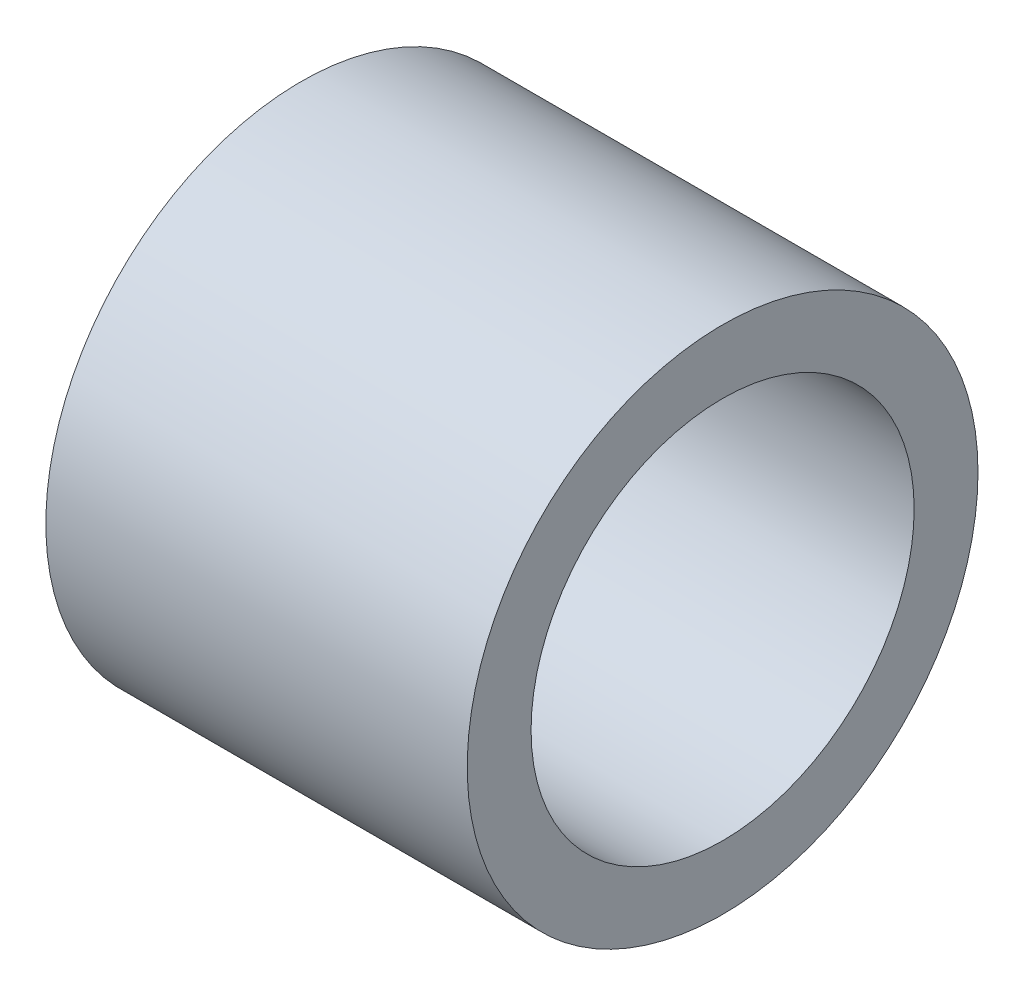
SolidWorks part; units mm, degrees
ref_plane "Front Plane" through (0, 0, 0) normal (0, 0, 1) x (1, 0, 0)
ref_plane "Top Plane" through (0, 0, 0) normal (0, 1, 0) x (1, 0, 0)
ref_plane "Right Plane" through (0, 0, 0) normal (1, 0, 0) x (0, 0, -1)
sketch "Sketch2" plane through (0, 0, 0) normal (1, 0, 0) x (0, 0, -1)
  circle A0 centre (0, 0) radius 7.5
  circle A1 centre (0, 0) radius 10
  dimension "D1" = 15
  dimension "D2" = 2.5
extrude "Boss-Extrude1" add sketch "Sketch2" along normal mid plane 16.5
